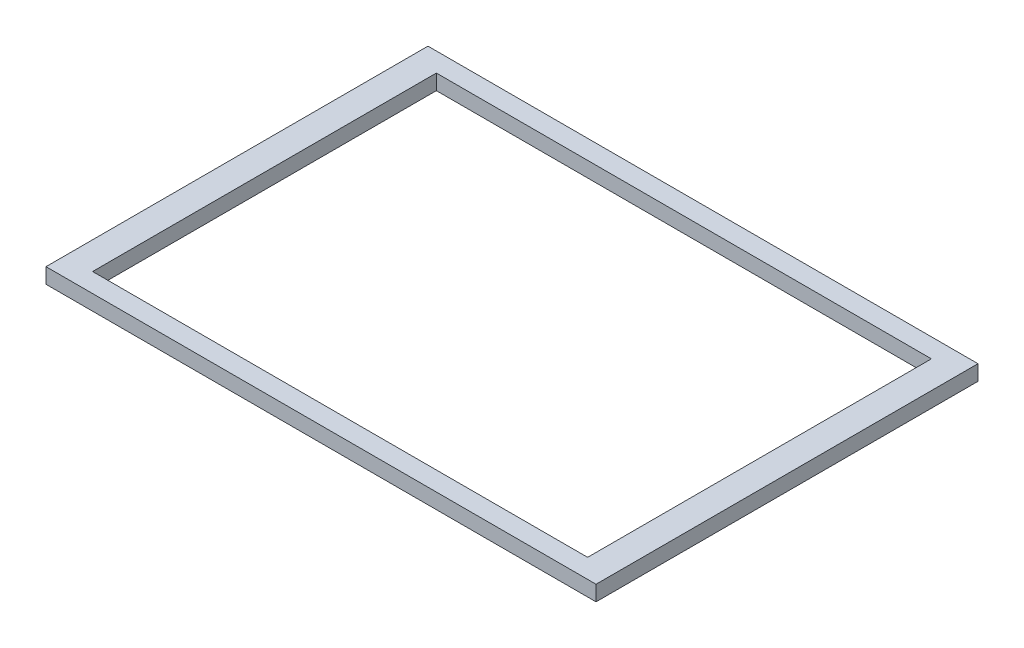
SolidWorks part; units mm, degrees
ref_plane "Front Plane" through (0, 0, 0) normal (0, 0, 1) x (1, 0, 0)
ref_plane "Top Plane" through (0, 0, 0) normal (0, 1, 0) x (1, 0, 0)
ref_plane "Right Plane" through (0, 0, 0) normal (1, 0, 0) x (0, 0, -1)
sketch "Sketch2" plane through (0, 0, 0) normal (0, 1, 0) x (1, 0, 0)
  line L1 (18, -12.5) -> (-18, -12.5)
  line L2 (18, -12.5) -> (18, 12.5)
  line L3 (18, 12.5) -> (-18, 12.5)
  line L4 (-18, -12.5) -> (-18, 12.5)
  line L5 (18, -12.5) -> (-18, 12.5) construction
  line L6 (18, 12.5) -> (-18, -12.5) construction
  line L7 (16.2, -11.25) -> (-16.2, -11.25)
  line L8 (16.2, -11.25) -> (16.2, 11.25)
  line L9 (16.2, 11.25) -> (-16.2, 11.25)
  line L10 (-16.2, -11.25) -> (-16.2, 11.25)
  line L11 (16.2, -11.25) -> (-16.2, 11.25) construction
  line L12 (16.2, 11.25) -> (-16.2, -11.25) construction
  point P0 (0, 0)
  point P6 (0, 0)
  dimension "D1" = 36
  dimension "D2" = 25
  dimension "D3" = 32.4
  dimension "D4" = 22.5
extrude "Boss-Extrude2" add sketch "Sketch2" along normal blind 1
ref_plane "Plane1" through (0, 0, 0) normal (-0.7071, 0.7071, 0) x (0.7071, 0.7071, 0)
ref_plane "Plane2" through (0, 0, 0) normal (0.7071, 0.7071, 0) x (0.7071, -0.7071, 0)
